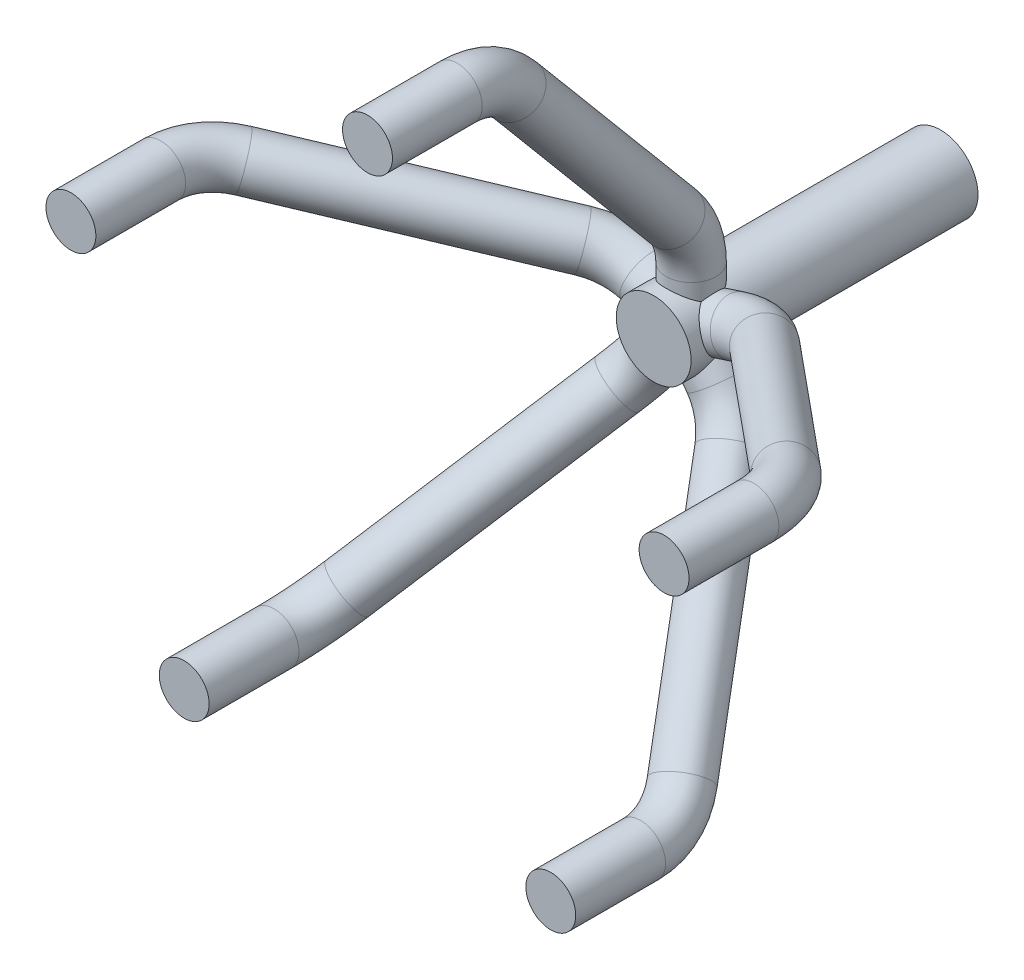
SolidWorks part; units mm, degrees
ref_plane "Piano frontale" through (0, 0, 0) normal (0, 0, 1) x (1, 0, 0)
ref_plane "Piano superiore" through (0, 0, 0) normal (0, 1, 0) x (1, 0, 0)
ref_plane "Piano destro" through (0, 0, 0) normal (1, 0, 0) x (0, 0, -1)
sketch "Schizzo1" plane through (0, 0, 0) normal (0, 0, 1) x (1, 0, 0)
  circle A0 centre (0, 0) radius 15
  dimension "D1" = 30
extrude "Estrusione-Estrusione1" add sketch "Schizzo1" along normal blind 115
sketch "Schizzo2" plane through (0, 0, 0) normal (1, 0, 0) x (0, 0, -1)
  line L0 (0, 0) -> (-245.7213, 0) construction
  line L1 (0, -15) -> (0, 15) construction
  line L2 (-170.7224, 114.2836) -> (-107.0187, 38.3645)
  line L3 (0, 15) -> (-115, 15) construction
  line L4 (-229.7145, 125) -> (-193.7037, 125)
  line L5 (-100, 19.0809) -> (-100, 15)
  arc A0 (-170.7224, 114.2836) -> (-193.7037, 125) centre (-193.7037, 95) ccw
  arc A1 (-100, 19.0809) -> (-107.0187, 38.3645) centre (-130, 19.0809) ccw
  dimension "D6" = 60
  dimension "D7" = 60
  dimension "D3" = 125
  dimension "D4" = 50
ref_plane "Piano1" through (0, 15, 0) normal (0, 1, 0) x (1, 0, 0)
sketch "Schizzo3" plane through (0, 15, 0) normal (0, 1, 0) x (1, 0, 0)
  circle A0 centre (0, -100) radius 10
  dimension "D1" = 20
sweep "Sweep1" add profiles "Schizzo3" path "Schizzo2"
sketch "Schizzo4" plane through (0, 15, 0) normal (0, -1, 0) x (1, 0, 0)
  circle A0 centre (0, 100) radius 10
  circle A1 centre (0, 100) radius 10 construction
extrude "Estrusione-Estrusione2" add sketch "Schizzo4" along normal up to surface up to face at (15, 0, 115)
pattern_circular "RipetizioneCircolare2" count 5 over 360 about axis through (0, 0, 115) along (0, 0, 1) of "Estrusione-Estrusione2"
pattern_circular "RipetizioneCircolare4" count 5 every 72 about axis through (0, 0, 0) along (0, 0, 1) of "Sweep1"
